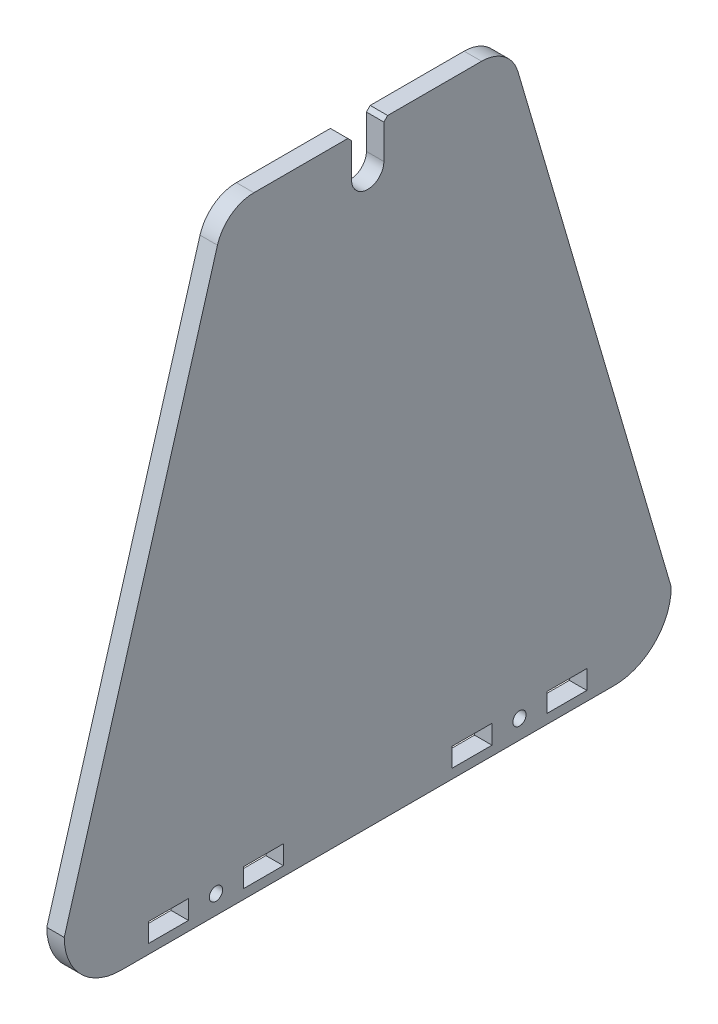
SolidWorks part; units mm, degrees
ref_plane "Front Plane" through (0, 0, 0) normal (0, 0, 1) x (1, 0, 0)
ref_plane "Top Plane" through (0, 0, 0) normal (0, 1, 0) x (1, 0, 0)
ref_plane "Right Plane" through (0, 0, 0) normal (1, 0, 0) x (0, 0, -1)
sketch "Sketch1" plane through (0, 0, 0) normal (1, 0, 0) x (0, 0, -1)
  line L0 (20.0034, 4.9939) -> (150.0034, 4.9939)
  line L1 (165.0034, 19.9939) -> (124.61, 157.8066)
  line L2 (115.0137, 164.9939) -> (90.2534, 164.9939)
  line L3 (90.2534, 164.9939) -> (89.2534, 163.9939)
  line L4 (89.2534, 163.9939) -> (89.2534, 154.9939)
  line L5 (80.7534, 154.9939) -> (80.7534, 163.9939)
  line L6 (80.7534, 163.9939) -> (79.7534, 164.9939)
  line L7 (79.7534, 164.9939) -> (54.9931, 164.9939)
  line L8 (45.3968, 157.8066) -> (5.0034, 19.9939)
  line L9 (27.2534, 7.4939) -> (37.7534, 7.4939)
  line L10 (37.7534, 7.4939) -> (37.7534, 12.4939)
  line L11 (37.7534, 12.4939) -> (27.2534, 12.4939)
  line L12 (27.2534, 12.4939) -> (27.2534, 7.4939)
  line L13 (62.7534, 7.4939) -> (52.2534, 7.4939)
  line L14 (52.2534, 7.4939) -> (52.2534, 12.4939)
  line L15 (52.2534, 12.4939) -> (62.7534, 12.4939)
  line L16 (62.7534, 12.4939) -> (62.7534, 7.4939)
  line L17 (142.7534, 7.4939) -> (132.2534, 7.4939)
  line L18 (132.2534, 7.4939) -> (132.2534, 12.4939)
  line L19 (132.2534, 12.4939) -> (142.7534, 12.4939)
  line L20 (142.7534, 12.4939) -> (142.7534, 7.4939)
  line L21 (107.2534, 7.4939) -> (117.7534, 7.4939)
  line L22 (117.7534, 7.4939) -> (117.7534, 12.4939)
  line L23 (117.7534, 12.4939) -> (107.2534, 12.4939)
  line L24 (107.2534, 12.4939) -> (107.2534, 7.4939)
  arc A0 (5.0034, 19.9939) -> (20.0034, 4.9939) centre (20.0034, 19.9939) ccw
  arc A1 (150.0034, 4.9939) -> (165.0034, 19.9939) centre (150.0034, 19.9939) ccw
  arc A2 (124.61, 157.8066) -> (115.0137, 164.9939) centre (115.0137, 154.9939) ccw
  arc A3 (80.7534, 154.9939) -> (89.2534, 154.9939) centre (85.0034, 154.9939) ccw
  arc A4 (54.9931, 164.9939) -> (45.3968, 157.8066) centre (54.9931, 154.9939) ccw
  circle A5 centre (45.0034, 9.9939) radius 1.75
  circle A6 centre (125.0034, 9.9939) radius 1.75
extrude "Extrude1" add sketch "Sketch1" along normal blind 4.6
